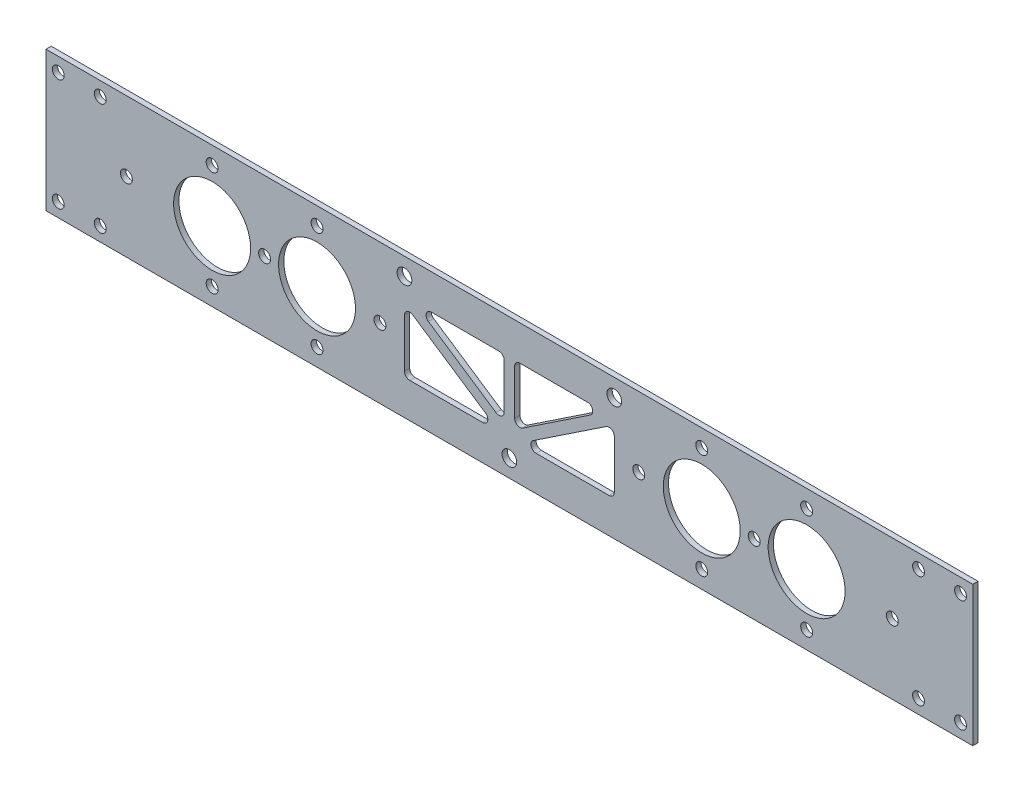
SolidWorks part; units mm, degrees
material "Thornel Mat VMA"
ref_plane "前视基准面" through (0, 0, 0) normal (0, 0, 1) x (1, 0, 0)
ref_plane "上视基准面" through (0, 0, 0) normal (0, 1, 0) x (1, 0, 0)
ref_plane "右视基准面" through (0, 0, 0) normal (1, 0, 0) x (0, 0, -1)
sketch "草图1" plane through (0, 0, 0) normal (0, 0, 1) x (1, 0, 0)
  line L1 (-132.5, 20) -> (132.5, 20)
  line L2 (-132.5, 20) -> (-132.5, -20)
  line L3 (-132.5, -20) -> (132.5, -20)
  line L4 (132.5, 20) -> (132.5, -20)
  line L5 (-132.5, 20) -> (132.5, -20) construction
  line L6 (-132.5, -20) -> (132.5, 20) construction
  point P0 (0, 0)
  dimension "D1" = 265
  dimension "D2" = 40
extrude "凸台-拉伸1" add sketch "草图1" along normal blind 1.5
sketch "草图2" plane through (0, 0, 1.5) normal (0, 0, 1) x (1, 0, 0)
  line L6 (30, -8.5) -> (30, 5.3944)
  line L7 (7.6583, -10) -> (28.5, -10)
  line L8 (27.6679, 6.6425) -> (6.8263, -7.2519)
  line L12 (3.8321, -5.6425) -> (23.1737, 7.2519)
  line L13 (1.5, 8.5) -> (1.5, -4.3944)
  line L14 (22.3417, 10) -> (3, 10)
  line L18 (-1.5, -4.3944) -> (-1.5, 8.5)
  line L19 (-23.1737, 7.2519) -> (-3.8321, -5.6425)
  line L20 (-3, 10) -> (-22.3417, 10)
  line L24 (-6.8263, -7.2519) -> (-27.6679, 6.6425)
  line L25 (-28.5, -10) -> (-7.6583, -10)
  line L26 (-30, 5.3944) -> (-30, -8.5)
  circle A2 centre (85, 0) radius 11
  circle A4 centre (55, 0) radius 11
  circle A9 centre (0, -15) radius 2.1
  arc A10 (28.5, -10) -> (30, -8.5) centre (28.5, -8.5) ccw
  arc A11 (6.8263, -7.2519) -> (7.6583, -10) centre (7.6583, -8.5) ccw
  arc A12 (30, 5.3944) -> (27.6679, 6.6425) centre (28.5, 5.3944) ccw
  circle A14 centre (30, 15) radius 2.1
  arc A20 (1.5, -4.3944) -> (3.8321, -5.6425) centre (3, -4.3944) ccw
  arc A21 (3, 10) -> (1.5, 8.5) centre (3, 8.5) ccw
  arc A22 (23.1737, 7.2519) -> (22.3417, 10) centre (22.3417, 8.5) ccw
  circle A25 centre (-30, 15) radius 2.1
  arc A26 (-3.8321, -5.6425) -> (-1.5, -4.3944) centre (-3, -4.3944) ccw
  arc A27 (-22.3417, 10) -> (-23.1737, 7.2519) centre (-22.3417, 8.5) ccw
  arc A28 (-1.5, 8.5) -> (-3, 10) centre (-3, 8.5) ccw
  circle A33 centre (-55, 0) radius 11
  arc A34 (-7.6583, -10) -> (-6.8263, -7.2519) centre (-7.6583, -8.5) ccw
  arc A35 (-30, -8.5) -> (-28.5, -10) centre (-28.5, -8.5) ccw
  arc A36 (-27.6679, 6.6425) -> (-30, 5.3944) centre (-28.5, 5.3944) ccw
  circle A37 centre (-85, 0) radius 11
extrude "切除-拉伸1" cut sketch "草图2" against normal through all
sketch "草图3" plane through (0, 0, 0) normal (0, 0, -1) x (-1, 0, 0)
  line L11 (-1.5, -4.3944) -> (-1.5, 8.5)
  line L16 (-3, 10) -> (-22.3417, 10)
  line L17 (-23.1737, 7.2519) -> (-3.8321, -5.6425)
  line L22 (-1.5, -4.3944) -> (-1.5, 8.5)
  line L23 (-3, 10) -> (-22.3417, 10)
  line L36 (-23.1737, 7.2519) -> (-3.8321, -5.6425)
  line L37 (30, -8.5) -> (30, 5.3944)
  line L38 (27.6679, 6.6425) -> (6.8263, -7.2519)
  line L39 (7.6583, -10) -> (28.5, -10)
  line L40 (30, -8.5) -> (30, 5.3944)
  line L41 (27.6679, 6.6425) -> (6.8263, -7.2519)
  line L42 (7.6583, -10) -> (28.5, -10)
  line L43 (3.8321, -5.6425) -> (23.1737, 7.2519)
  line L44 (22.3417, 10) -> (3, 10)
  line L45 (1.5, 8.5) -> (1.5, -4.3944)
  line L46 (3.8321, -5.6425) -> (23.1737, 7.2519)
  line L47 (22.3417, 10) -> (3, 10)
  line L48 (1.5, 8.5) -> (1.5, -4.3944)
  line L49 (-6.8263, -7.2519) -> (-27.6679, 6.6425)
  line L50 (-30, 5.3944) -> (-30, -8.5)
  line L51 (-28.5, -10) -> (-7.6583, -10)
  line L52 (-6.8263, -7.2519) -> (-27.6679, 6.6425)
  line L53 (-30, 5.3944) -> (-30, -8.5)
  line L54 (-28.5, -10) -> (-7.6583, -10)
  circle A3 centre (0, -15) radius 2.1
  circle A5 centre (0, -15) radius 2.1
  circle A31 centre (-30, 15) radius 2.1
  circle A33 centre (-30, 15) radius 2.1
  circle A35 centre (30, 15) radius 2.1
  circle A37 centre (30, 15) radius 2.1
  circle A39 centre (85, 0) radius 11
  circle A41 centre (85, 0) radius 11
  arc A43 (-1.5, 8.5) -> (-3, 10) centre (-3, 8.5) ccw
  arc A45 (-22.3417, 10) -> (-23.1737, 7.2519) centre (-22.3417, 8.5) ccw
  arc A47 (-3.8321, -5.6425) -> (-1.5, -4.3944) centre (-3, -4.3944) ccw
  arc A49 (-1.5, 8.5) -> (-3, 10) centre (-3, 8.5) ccw
  arc A51 (-22.3417, 10) -> (-23.1737, 7.2519) centre (-22.3417, 8.5) ccw
  arc A53 (-3.8321, -5.6425) -> (-1.5, -4.3944) centre (-3, -4.3944) ccw
  arc A55 (30, 5.3944) -> (27.6679, 6.6425) centre (28.5, 5.3944) ccw
  arc A57 (6.8263, -7.2519) -> (7.6583, -10) centre (7.6583, -8.5) ccw
  arc A59 (28.5, -10) -> (30, -8.5) centre (28.5, -8.5) ccw
  arc A61 (30, 5.3944) -> (27.6679, 6.6425) centre (28.5, 5.3944) ccw
  arc A63 (6.8263, -7.2519) -> (7.6583, -10) centre (7.6583, -8.5) ccw
  arc A65 (28.5, -10) -> (30, -8.5) centre (28.5, -8.5) ccw
  arc A67 (23.1737, 7.2519) -> (22.3417, 10) centre (22.3417, 8.5) ccw
  arc A69 (3, 10) -> (1.5, 8.5) centre (3, 8.5) ccw
  arc A71 (1.5, -4.3944) -> (3.8321, -5.6425) centre (3, -4.3944) ccw
  arc A73 (23.1737, 7.2519) -> (22.3417, 10) centre (22.3417, 8.5) ccw
  arc A75 (3, 10) -> (1.5, 8.5) centre (3, 8.5) ccw
  arc A77 (1.5, -4.3944) -> (3.8321, -5.6425) centre (3, -4.3944) ccw
  arc A79 (-27.6679, 6.6425) -> (-30, 5.3944) centre (-28.5, 5.3944) ccw
  arc A81 (-30, -8.5) -> (-28.5, -10) centre (-28.5, -8.5) ccw
  arc A101 (-7.6583, -10) -> (-6.8263, -7.2519) centre (-7.6583, -8.5) ccw
  arc A102 (-27.6679, 6.6425) -> (-30, 5.3944) centre (-28.5, 5.3944) ccw
  arc A103 (-30, -8.5) -> (-28.5, -10) centre (-28.5, -8.5) ccw
  arc A104 (-7.6583, -10) -> (-6.8263, -7.2519) centre (-7.6583, -8.5) ccw
  circle A105 centre (55, 0) radius 11
  circle A106 centre (55, 0) radius 11
  circle A107 centre (-55, 0) radius 11
  circle A108 centre (-55, 0) radius 11
  circle A109 centre (-85, 0) radius 11
  circle A110 centre (-85, 0) radius 11
  circle A111 centre (-55, -15) radius 1.7
  circle A112 centre (-55, -15) radius 1.7
  circle A113 centre (55, 15) radius 1.7
  circle A114 centre (55, 15) radius 1.7
  circle A115 centre (-70, 0) radius 1.7
  circle A116 centre (-70, 0) radius 1.7
  circle A117 centre (-55, 15) radius 1.7
  circle A118 centre (-55, 15) radius 1.7
  circle A119 centre (85, 15) radius 1.7
  circle A120 centre (85, 15) radius 1.7
  circle A121 centre (-85, 15) radius 1.7
  circle A122 centre (-85, 15) radius 1.7
  circle A123 centre (55, -15) radius 1.7
  circle A124 centre (55, -15) radius 1.7
  circle A125 centre (85, -15) radius 1.7
  circle A126 centre (85, -15) radius 1.7
  circle A127 centre (-37, 0) radius 1.7
  circle A128 centre (-37, 0) radius 1.7
  circle A129 centre (37, 0) radius 1.7
  circle A130 centre (37, 0) radius 1.7
  circle A131 centre (109.5, 0) radius 1.7
  circle A132 centre (109.5, 0) radius 1.7
  circle A133 centre (-85, -15) radius 1.7
  circle A134 centre (-85, -15) radius 1.7
  circle A135 centre (-109.5, 0) radius 1.7
  circle A136 centre (-109.5, 0) radius 1.7
  circle A137 centre (70, 0) radius 1.7
  circle A138 centre (70, 0) radius 1.7
  dimension "D1" = 0
  dimension "D2" = 0
  dimension "D3" = 0
  dimension "D4" = 0
  dimension "D5" = 0
  dimension "D6" = 0
  dimension "D7" = 0
  dimension "D8" = 0
  dimension "D9" = 0
  dimension "D10" = 0
  dimension "D11" = 0
  dimension "D12" = 0
  dimension "D13" = 0
  dimension "D14" = 0
  dimension "D15" = 0
  dimension "D16" = 0
  dimension "D17" = 0
  dimension "D18" = 0
  dimension "D19" = 0
  dimension "D20" = 0
  dimension "D21" = 0
  dimension "D22" = 0
  dimension "D23" = 0
  dimension "D24" = 0
  dimension "D25" = 0
extrude "切除-拉伸2" cut sketch "草图3" against normal through all
sketch "草图4" plane through (0, 0, 0) normal (0, 0, -1) x (-1, 0, 0)
  line L0 (0, 0) -> (0, -20) construction
  line L1 (132.5, -20) -> (-132.5, -20) construction
  circle A0 centre (-129, -16) radius 1.7
  circle A1 centre (-129, -16) radius 1.25
  circle A2 centre (-129, -16) radius 1.25 construction
  circle A3 centre (-129, 16) radius 1.25
  circle A4 centre (-129, 16) radius 1.25 construction
  circle A5 centre (-117, -16) radius 1.25
  circle A6 centre (-117, -16) radius 1.25 construction
  circle A7 centre (-117, 16) radius 1.25
  circle A8 centre (-117, 16) radius 1.25 construction
  circle A9 centre (-129, 16) radius 1.7
  circle A10 centre (-117, -16) radius 1.7
  circle A11 centre (-117, 16) radius 1.7
  circle A12 centre (117, 16) radius 1.25 construction
  circle A13 centre (117, -16) radius 1.25 construction
  circle A14 centre (129, 16) radius 1.25 construction
  circle A15 centre (129, -16) radius 1.25 construction
  circle A16 centre (117, 16) radius 1.7
  circle A17 centre (117, -16) radius 1.7
  circle A18 centre (129, 16) radius 1.7
  circle A19 centre (129, -16) radius 1.7
  dimension "D1" = 0
  dimension "D2" = 0
  dimension "D3" = 0
  dimension "D4" = 0
  dimension "D5" = 0.45
extrude "切除-拉伸3" cut sketch "草图4" against normal through all
